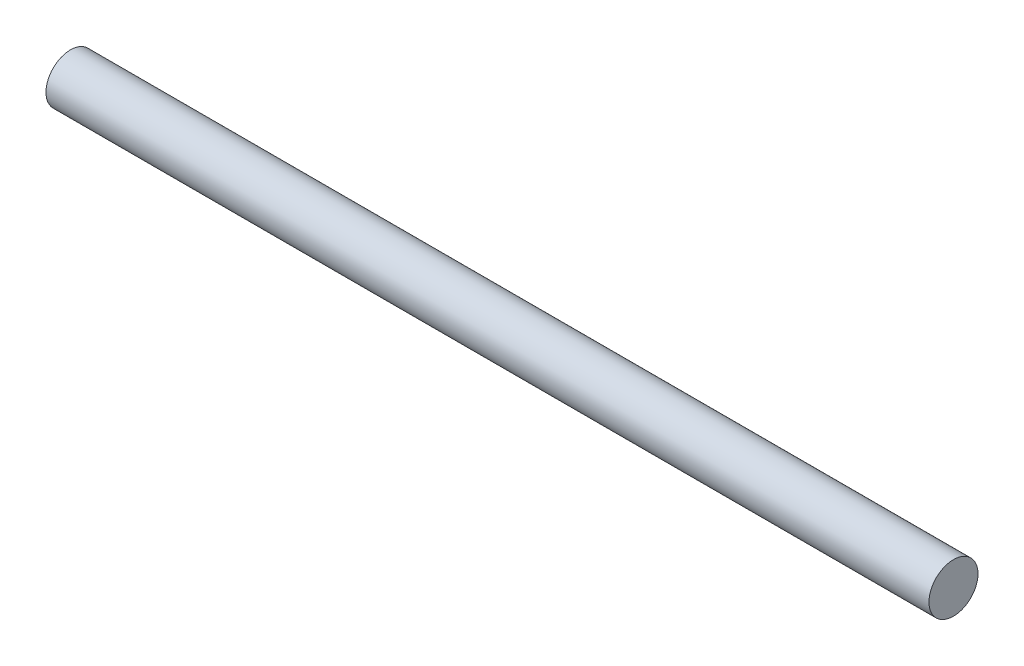
SolidWorks part; units mm, degrees
ref_plane "Front Plane" through (0, 0, 0) normal (0, 0, 1) x (1, 0, 0)
ref_plane "Top Plane" through (0, 0, 0) normal (0, 1, 0) x (1, 0, 0)
ref_plane "Right Plane" through (0, 0, 0) normal (1, 0, 0) x (0, 0, -1)
sketch "Sketch1" plane through (0, 0, 0) normal (1, 0, 0) x (0, 0, -1)
  circle A0 centre (0, 0) radius 7.5
extrude "Boss-Extrude1" add sketch "Sketch1" along normal blind 270
